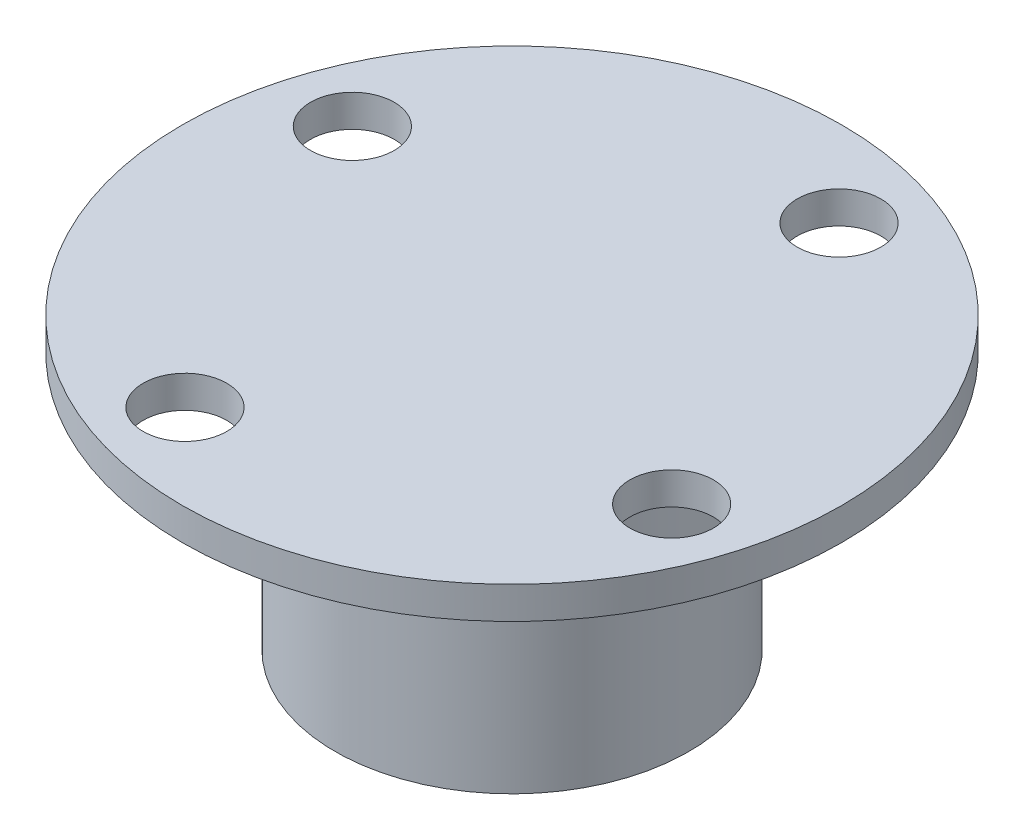
SolidWorks part; units mm, degrees
ref_plane "Plan de face" through (0, 0, 0) normal (0, 0, 1) x (1, 0, 0)
ref_plane "Plan de dessus" through (0, 0, 0) normal (0, 1, 0) x (1, 0, 0)
ref_plane "Plan de droite" through (0, 0, 0) normal (1, 0, 0) x (0, 0, -1)
sketch "Esquisse1" plane through (0, -38.6013, 0) normal (0, -1, 0) x (1, 0, 0)
  circle A0 centre (14.0172, 17.25) radius 10.25
  arc A1 (9.5205, 8.039) -> (18.514, 26.461) centre (14.0172, 17.25) ccw construction
  dimension "D1" = 20.5
  dimension "D2" = 0
extrude "Boss.-Extru.1" add sketch "Esquisse1" along normal blind 1
hole_wizard "Dégagement M21" positions "Esquisse3" profile "Esquisse4" hole size "M2" standard "Ansi Metric" end condition up to next
sketch "Esquisse3" plane through (0, -39.6013, 0) normal (0, -1, 0) x (-1, 0, 0)
  circle A0 centre (-14.0172, -17.25) radius 8 construction
  point P0 (-11.4155, -24.8151)
  point P7 (0, 0)
  point P8 (-14.7696, -25.226)
  point P9 (-15.3882, -25.25)
  dimension "D1" = 16
sketch "Esquisse4" plane through (11.4155, -39.6013, 24.8151) normal (1, 0, 0) x (0, 0, -1)
  line L0 (0, 0) -> (0, 1.001)
  line L1 (0, 1.001) -> (1.3, 1.001)
  line L2 (1.3, 1.001) -> (1.3, 0)
  line L5 (1.3, 0) -> (0, 0)
  line L11 (0, -6.35) -> (0, 107.95) construction
  dimension "Diamètre du perçage jusqu'au prochain" = 2.6
  dimension "Profondeur du perçage jusqu'au prochain" = 1.001
pattern_circular "Répétition circulaire1" count 4 over 360 about axis through (14.0172, 0, 17.25) along (0, 1, 0) of "Dégagement M21"
sketch "Esquisse9" plane through (0, -39.6013, 0) normal (0, -1, 0) x (-1, 0, 0)
  circle A0 centre (-14.0172, -17.25) radius 5.5
  dimension "D1" = 11
extrude "Boss.-Extru.4" add sketch "Esquisse9" along normal blind 8
sketch "Esquisse10" plane through (0, -47.6013, 0) normal (0, -1, 0) x (1, 0, 0)
  line L0 (11.9048, 19.85) -> (16.1297, 19.85)
  arc A0 (11.9048, 19.85) -> (16.1297, 19.85) centre (14.0172, 17.25) ccw
  dimension "D1" = 6.7
  dimension "D2" = 2.6
extrude "Enlèv. mat.-Extru.1" cut sketch "Esquisse10" against normal blind 6
fillet "Congé1" radius 0.5 1 edges at (14.0172, -39.6013, 11.75)
